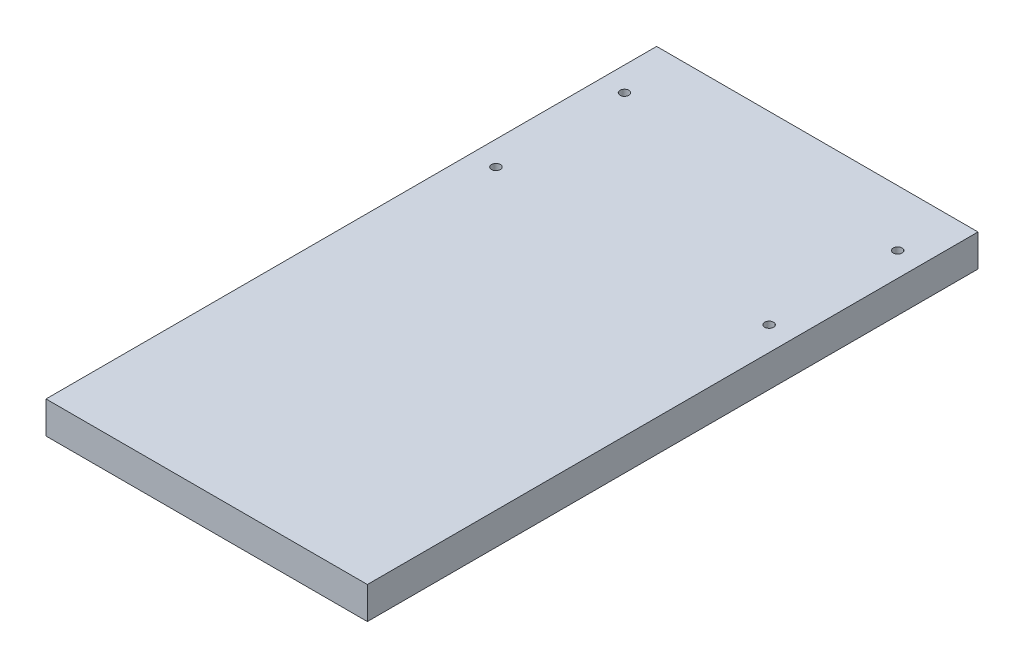
SolidWorks part; units mm, degrees
ref_plane "Front Plane" through (0, 0, 0) normal (0, 0, 1) x (1, 0, 0)
ref_plane "Top Plane" through (0, 0, 0) normal (0, 1, 0) x (1, 0, 0)
ref_plane "Right Plane" through (0, 0, 0) normal (1, 0, 0) x (0, 0, -1)
sketch "Sketch1" plane through (0, 0, 0) normal (0, 1, 0) x (1, 0, 0)
  line L1 (-50, -95) -> (50, -95)
  line L2 (-50, -95) -> (-50, 95)
  line L3 (-50, 95) -> (50, 95)
  line L4 (50, -95) -> (50, 95)
  line L5 (-50, -95) -> (50, 95) construction
  line L6 (-50, 95) -> (50, -95) construction
  point P0 (0, 0)
  point P8 (0, 0)
  point P9 (0, 0)
  dimension "D1" = 100
  dimension "D2" = 190
extrude "Boss-Extrude1" add sketch "Sketch1" along normal blind 10
sketch "Sketch2" plane through (0, 10, 0) normal (0, 1, 0) x (1, 0, 0)
  line L0 (-42.5, 37.5) -> (-42.5, 77.5)
  line L1 (-50, 95) -> (50, 95) construction
  line L4 (0, 95) -> (0, -95)
  line L5 (-50, -95) -> (50, -95) construction
  circle A0 centre (-42.5, 77.5) radius 1.375
  circle A1 centre (-42.5, 37.5) radius 1.375
  circle A2 centre (42.5, 37.5) radius 1.375
  circle A3 centre (42.5, 77.5) radius 1.375
  point P8 (-42.5, 57.5)
  dimension "D1" = 42.5
  dimension "D2" = 37.5
  dimension "D3" = 40
extrude "Cut-Extrude1" cut sketch "Sketch2" against normal blind 7
